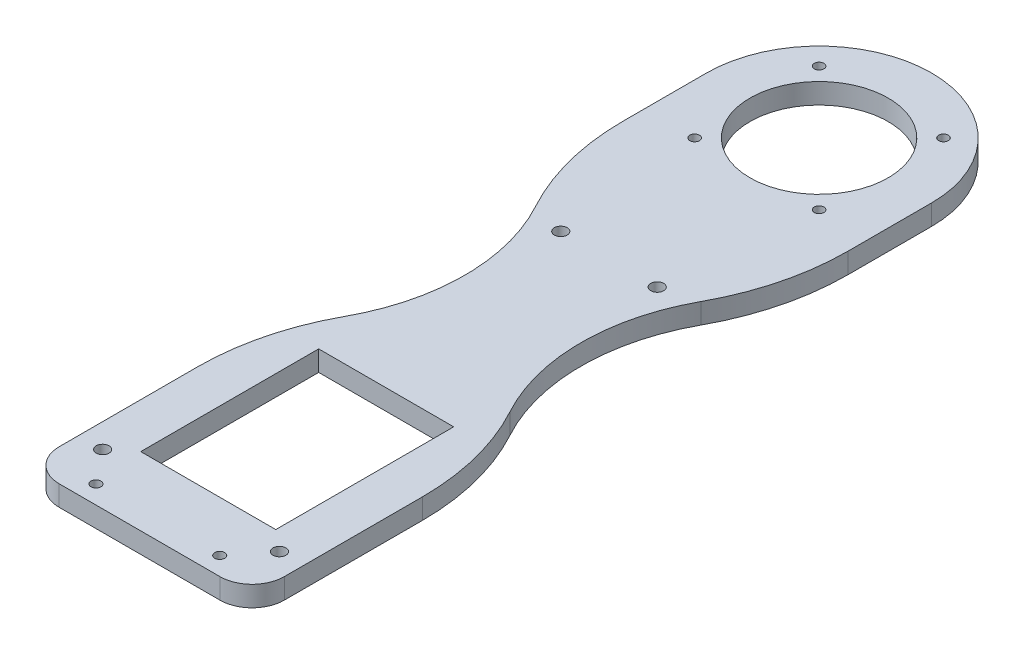
SolidWorks part; units mm, degrees
ref_plane "Front Plane" through (0, 0, 0) normal (0, 0, 1) x (1, 0, 0)
ref_plane "Top Plane" through (0, 0, 0) normal (0, 1, 0) x (1, 0, 0)
ref_plane "Right Plane" through (0, 0, 0) normal (1, 0, 0) x (0, 0, -1)
sketch "Sketch1" plane through (0, 0, 0) normal (0, 1, 0) x (1, 0, 0)
  line L0 (-35, 0) -> (-35, -211.35)
  line L1 (-35, -211.35) -> (35, -211.35)
  line L2 (35, -211.35) -> (35, 0)
  circle A0 centre (0, 0) radius 35
  point P3 (0, -211.35)
  dimension "D1" = 70
  dimension "D2" = 70
  dimension "D3" = 211.35
extrude "Boss-Extrude1" add sketch "Sketch1" along normal mid plane 6.35
sketch "Sketch2" plane through (0, 3.175, 0) normal (0, 1, 0) x (1, 0, 0)
  circle A0 centre (0, 0) radius 21.5
  dimension "D1" = 43
extrude "Cut-Extrude1" cut sketch "Sketch2" against normal through all
sketch "Sketch3" plane through (0, 3.175, 0) normal (0, 1, 0) x (1, 0, 0)
  line L1 (21, -190) -> (-21, -190)
  line L2 (21, -190) -> (21, -134.65)
  line L3 (21, -134.65) -> (-21, -134.65)
  line L4 (-21, -190) -> (-21, -134.65)
  line L5 (21, -190) -> (-21, -134.65) construction
  line L6 (21, -134.65) -> (-21, -190) construction
  line L11 (-35, -211.35) -> (35, -211.35) construction
  point P0 (0, -162.325)
  dimension "D1" = 21.35
  dimension "D2" = 42
  dimension "48" = 55.35
extrude "Cut-Extrude2" cut sketch "Sketch3" against normal through all contours L4 L1 L2 L3
sketch "Sketch4" plane through (0, -3.175, 0) normal (0, -1, 0) x (1, 0, 0)
  line L0 (19.35, 19.35) -> (-19.35, 19.35) construction
  line L1 (-19.35, 19.35) -> (-19.35, -19.35) construction
  line L2 (-19.35, -19.35) -> (19.35, -19.35) construction
  line L3 (19.35, -19.35) -> (19.35, 19.35) construction
  circle A0 centre (-19.35, 19.35) radius 1.5
  circle A1 centre (19.35, 19.35) radius 1.5
  circle A2 centre (19.35, -19.35) radius 1.5
  circle A3 centre (-19.35, -19.35) radius 1.5
  point P2 (0, 19.35)
  point P5 (-19.35, 0)
  dimension "D2" = 3
  dimension "D1" = 38.7
extrude "Cut-Extrude3" cut sketch "Sketch4" against normal through all
fillet "Fillet1" radius 10 2 edges at (-35, 0, 211.35) (35, 0, 211.35)
sketch "Sketch5" plane through (0, 3.175, 0) normal (0, 1, 0) x (1, 0, 0)
  circle A0 centre (15, -65.35) radius 2
  circle A1 centre (-15, -65.35) radius 2
  circle A2 centre (27.5, -195.35) radius 2
  circle A3 centre (-27.5, -195.35) radius 2
extrude "Cut-Extrude4" cut sketch "Sketch5" against normal through all
sketch "Sketch6" plane through (0, 3.175, 0) normal (0, 1, 0) x (1, 0, 0)
  line L0 (-35, -134.65) -> (-35, -49.65)
  line L1 (-35, 0) -> (-35, -201.35) construction
  arc A0 (-35, -134.65) -> (-35, -49.65) centre (-80, -92.15) ccw
  point P5 (0, 0)
  dimension "D1" = 85
  dimension "D2" = 45
extrude "Cut-Extrude5" cut sketch "Sketch6" against normal through all
mirror "Mirror1" about plane through (0, 0, 0) normal (1, 0, 0) of "Cut-Extrude5"
fillet "Fillet2" radius 76 4 edges at (-35, 0, 49.65) (-35, 0, 134.65) (35, 0, 134.65) (35, 0, 49.65)
sketch "Sketch7" plane through (0, 3.175, 0) normal (0, 1, 0) x (1, 0, 0)
  circle A0 centre (-19.25, -205.675) radius 1.55
  circle A1 centre (19.25, -205.675) radius 1.55
  dimension "D1" = 3.1
extrude "Cut-Extrude6" cut sketch "Sketch7" against normal blind 10
